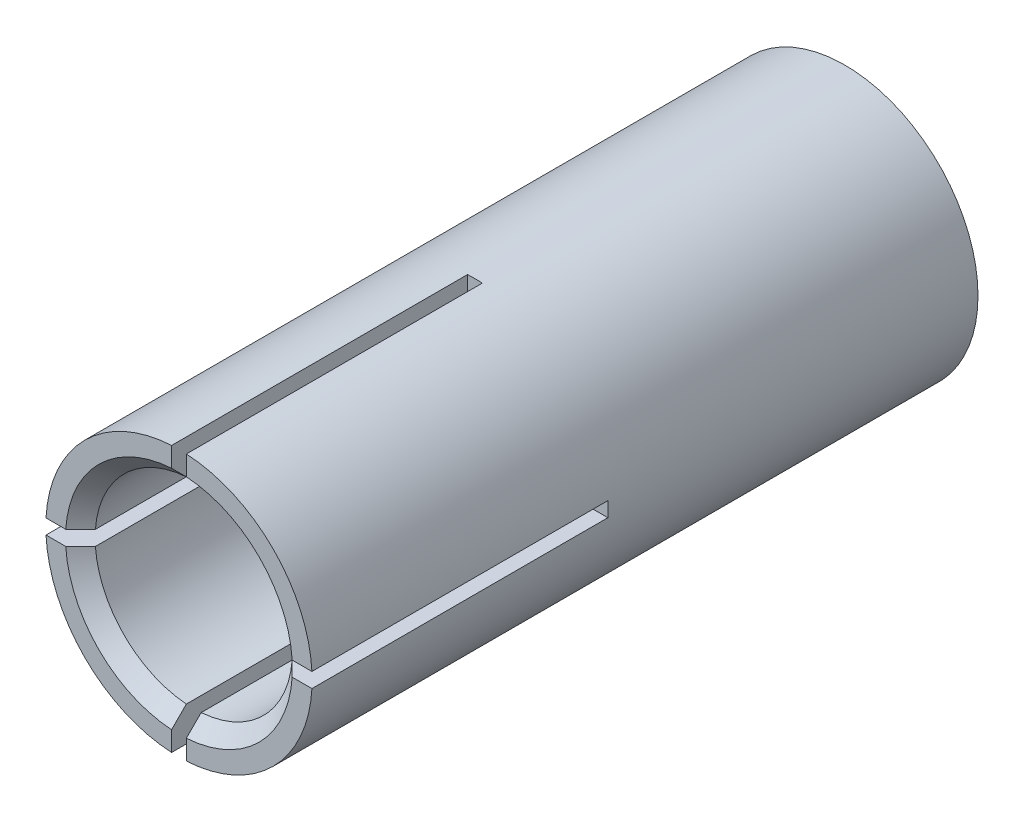
SolidWorks part; units mm, degrees
ref_plane "Front Plane" through (0, 0, 0) normal (0, 0, 1) x (1, 0, 0)
ref_plane "Top Plane" through (0, 0, 0) normal (0, 1, 0) x (1, 0, 0)
ref_plane "Right Plane" through (0, 0, 0) normal (1, 0, 0) x (0, 0, -1)
sketch "Sketch1" plane through (0, 0, 0) normal (0, 0, 1) x (1, 0, 0)
  circle A0 centre (0, 0) radius 9
  dimension "D1" = 18
extrude "Boss-Extrude1" add sketch "Sketch1" along normal blind 45
sketch "Sketch2" plane through (0, 0, 45) normal (0, 0, 1) x (1, 0, 0)
  circle A0 centre (0, 0) radius 6.6675
  dimension "D1" = 13.335
extrude "Cut-Extrude1" cut sketch "Sketch2" against normal blind 40
chamfer "Chamfer1" distance 1 angle 45 1 edges at (6.6675, 0, 45)
sketch "Sketch3" plane through (0, 0, 45) normal (0, 0, 1) x (1, 0, 0)
  line L1 (-11.3068, 0.5) -> (11.3068, 0.5)
  line L2 (-11.3068, 0.5) -> (-11.3068, -0.5)
  line L3 (-11.3068, -0.5) -> (11.3068, -0.5)
  line L4 (11.3068, 0.5) -> (11.3068, -0.5)
  line L5 (-11.3068, 0.5) -> (11.3068, -0.5) construction
  line L6 (-11.3068, -0.5) -> (11.3068, 0.5) construction
  line L7 (-0.5, 11.5725) -> (0.5, 11.5725)
  line L8 (-0.5, 11.5725) -> (-0.5, -11.5725)
  line L9 (-0.5, -11.5725) -> (0.5, -11.5725)
  line L10 (0.5, 11.5725) -> (0.5, -11.5725)
  line L11 (-0.5, 11.5725) -> (0.5, -11.5725) construction
  line L12 (-0.5, -11.5725) -> (0.5, 11.5725) construction
  point P0 (0, 0)
  point P6 (0, 0)
  dimension "D1" = 1
  dimension "D2" = 1
extrude "Cut-Extrude2" cut sketch "Sketch3" against normal blind 20
